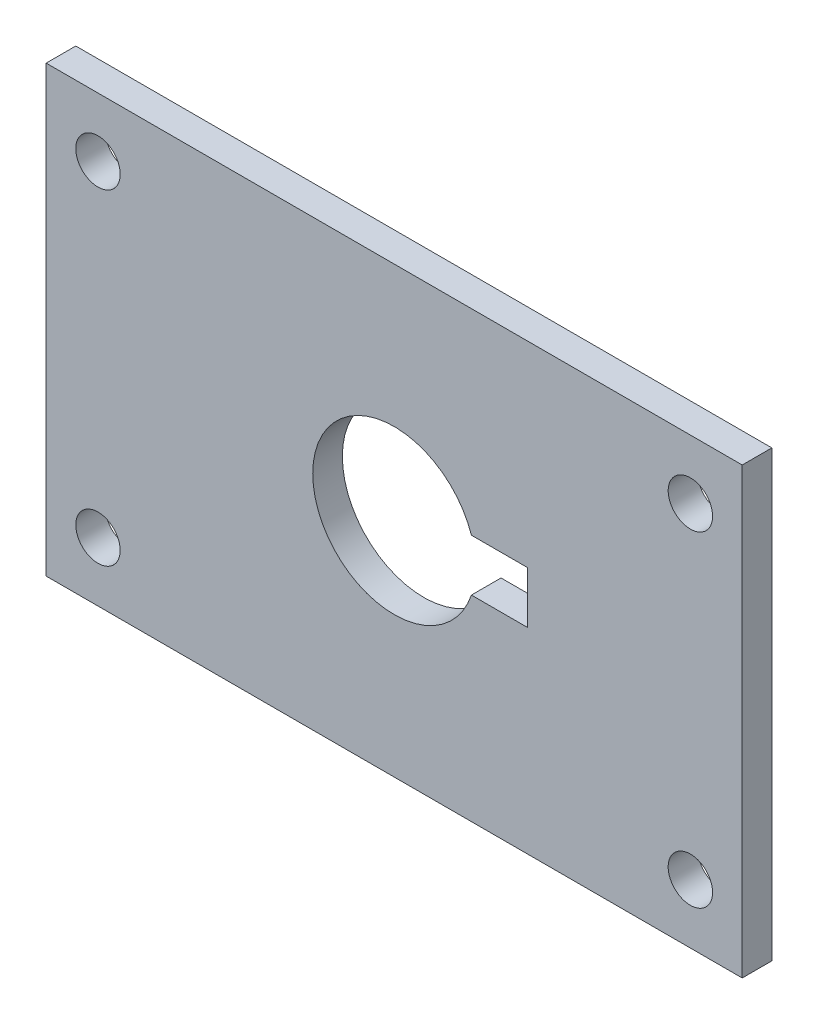
SolidWorks part; units mm, degrees
ref_plane "Спереди" through (0, 0, 0) normal (0, 0, 1) x (1, 0, 0)
ref_plane "Сверху" through (0, 0, 0) normal (0, 1, 0) x (1, 0, 0)
ref_plane "Справа" through (0, 0, 0) normal (1, 0, 0) x (0, 0, -1)
sketch "Эскиз1" plane through (0, 0, 0) normal (0, 0, 1) x (1, 0, 0)
  line L1 (0, 0) -> (47, 0)
  line L2 (0, 0) -> (0, 30)
  line L3 (0, 30) -> (47, 30)
  line L4 (47, 0) -> (47, 30)
  dimension "D1" = 47
  dimension "D2" = 30
extrude "Бобышка-Вытянуть1" add sketch "Эскиз1" along normal blind 2
sketch "Эскиз2" plane through (0, 0, 2) normal (0, 0, 1) x (1, 0, 0)
  line L0 (0, 0) -> (47, 0) construction
  line L1 (0, 30) -> (0, 0) construction
  circle A0 centre (23.5, 15) radius 5.5
  point P4 (23.5, 0)
  point P7 (0, 15)
  dimension "D1" = 11
  dimension "D2" = 0
  dimension "D3" = 0
extrude "Вырез-Вытянуть1" cut sketch "Эскиз2" against normal through all
sketch "Эскиз3" plane through (0, 0, 2) normal (0, 0, 1) x (1, 0, 0)
  line L1 (25.5, 16.75) -> (32.5, 16.75)
  line L2 (25.5, 16.75) -> (25.5, 13.25)
  line L3 (25.5, 13.25) -> (32.5, 13.25)
  line L4 (32.5, 16.75) -> (32.5, 13.25)
  line L5 (25.5, 16.75) -> (32.5, 13.25) construction
  line L6 (25.5, 13.25) -> (32.5, 16.75) construction
  circle A0 centre (23.5, 15) radius 5.5 construction
  point P0 (29, 15)
  dimension "D1" = 3.5
  dimension "D2" = 7
extrude "Вырез-Вытянуть2" cut sketch "Эскиз3" against normal through all
sketch "Эскиз4" plane through (0, 0, 2) normal (0, 0, 1) x (1, 0, 0)
  circle A0 centre (3.5, 4) radius 1.5
  arc A1 (28.7142, 16.75) -> (28.7142, 13.25) centre (23.5, 15) ccw construction
  circle A2 centre (43.5, 4) radius 1.5
  circle A3 centre (43.5, 26) radius 1.5
  circle A4 centre (3.5, 26) radius 1.5
  dimension "D1" = 3
  dimension "D2" = 20
  dimension "D3" = 11
  dimension "D4" = 2
  dimension "D5" = 2
extrude "Вырез-Вытянуть3" cut sketch "Эскиз4" against normal through all
